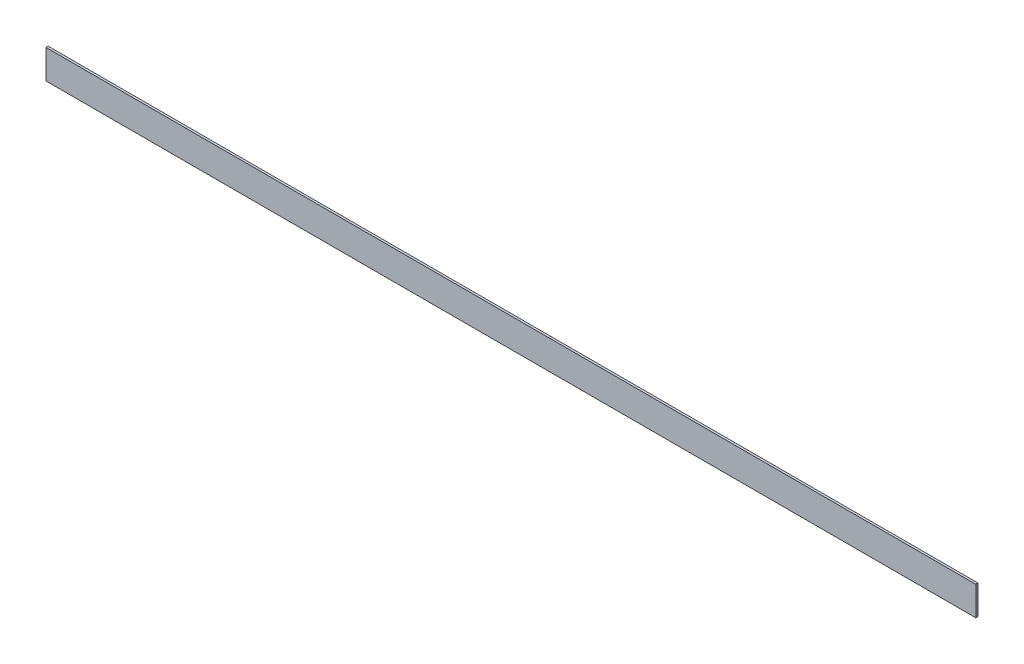
SolidWorks part; units mm, degrees
ref_plane "Front Plane" through (0, 0, 0) normal (0, 0, 1) x (1, 0, 0)
ref_plane "Top Plane" through (0, 0, 0) normal (0, 1, 0) x (1, 0, 0)
ref_plane "Right Plane" through (0, 0, 0) normal (1, 0, 0) x (0, 0, -1)
other "Configuration Table"
sketch "Sketch1" plane through (0, 0, 0) normal (0, 0, 1) x (1, 0, 0)
  line L1 (30, 1950) -> (670, 1950)
  line L2 (30, 1950) -> (30, 1970)
  line L3 (30, 1970) -> (670, 1970)
  line L4 (670, 1950) -> (670, 1970)
extrude "OVEN_panel_ust_serit_1" add sketch "Sketch1" along normal blind 1.5 from offset 38.5 separate body
